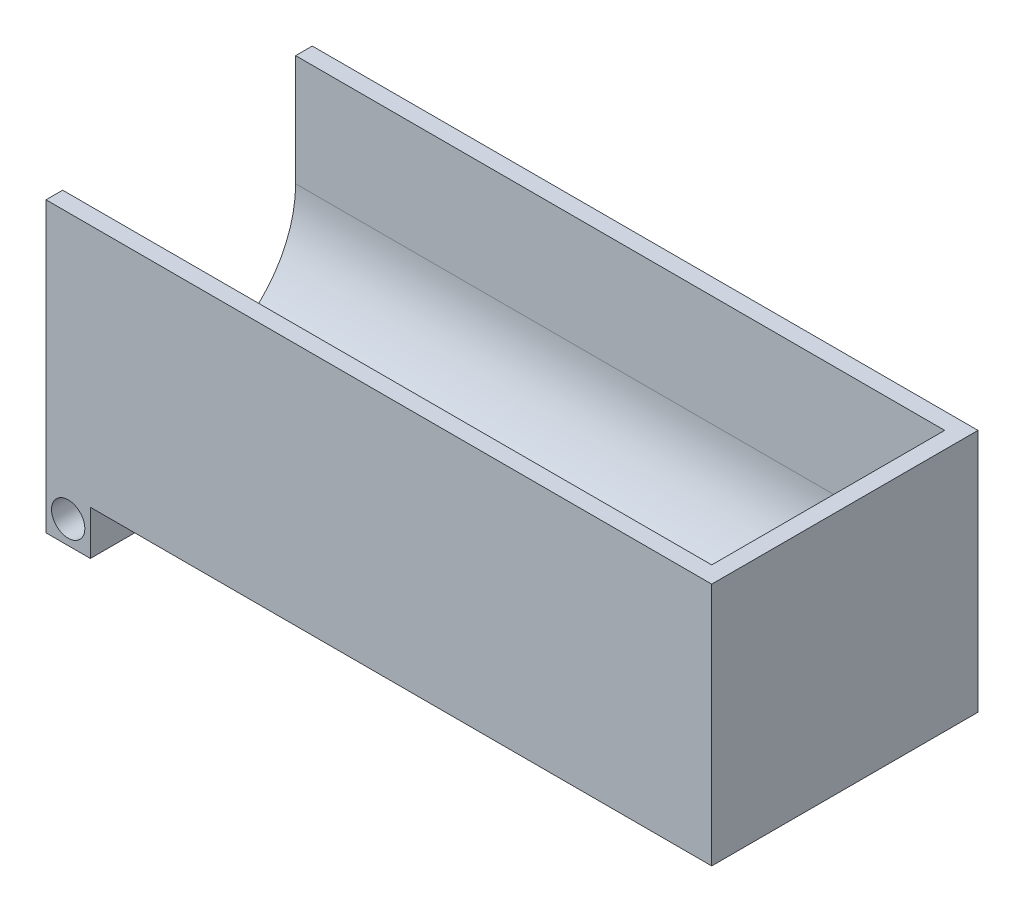
SolidWorks part; units mm, degrees
ref_plane "Front Plane" through (0, 0, 0) normal (0, 0, 1) x (1, 0, 0)
ref_plane "Top Plane" through (0, 0, 0) normal (0, 1, 0) x (1, 0, 0)
ref_plane "Right Plane" through (0, 0, 0) normal (1, 0, 0) x (0, 0, -1)
sketch "Sketch1" plane through (0, 0, 0) normal (1, 0, 0) x (0, 0, -1)
  line L0 (21, 0) -> (24, 0)
  line L1 (24, 0) -> (24, -24)
  line L2 (24, -24) -> (-24, -24)
  line L3 (-24, -24) -> (-24, 0)
  line L4 (-24, 0) -> (-21, 0)
  arc A0 (21, 0) -> (-21, 0) centre (0, 0) cw
  dimension "D3" = 21
  dimension "D1" = 3
  dimension "D2" = 3
  dimension "D4" = 24
extrude "Boss-Extrude1" add sketch "Sketch1" along normal blind 120
sketch "Sketch2" plane through (0, 0, 24) normal (0, 0, 1) x (1, 0, 0)
  line L1 (0, -24) -> (8, -24)
  line L2 (0, -24) -> (0, -32)
  line L3 (0, -32) -> (8, -32)
  line L4 (8, -24) -> (8, -32)
  dimension "D1" = 8
  dimension "D2" = 8
extrude "Boss-Extrude2" add sketch "Sketch2" against normal blind 48
sketch "Sketch3" plane through (0, 0, 24) normal (0, 0, 1) x (1, 0, 0)
  line L0 (0, -32) -> (8, -32) construction
  circle A0 centre (4, -27.8358) radius 3
  point P5 (4, -32)
  dimension "D1" = 6
extrude "Cut-Extrude1" cut sketch "Sketch3" against normal up to next
sketch "Sketch4" plane through (120, 0, 0) normal (1, 0, 0) x (0, 0, -1)
  line L1 (24, 0) -> (-24, 0)
  line L2 (24, 0) -> (24, -24)
  line L3 (24, -24) -> (-24, -24)
  line L4 (-24, 0) -> (-24, -24)
extrude "Boss-Extrude3" add sketch "Sketch4" against normal blind 3
sketch "Sketch5" plane through (0, -24, 0) normal (0, -1, 0) x (1, 0, 0)
  line L0 (120, -24) -> (8, -24) construction
  line L1 (15.3705, -13.3) -> (19.6916, -13.3)
  line L2 (15.3705, -13.3) -> (15.3705, -10.3)
  line L3 (15.3705, -10.3) -> (19.6916, -10.3)
  line L4 (19.6916, -13.3) -> (19.6916, -10.3)
  dimension "D1" = 10.7
  dimension "D2" = 3
extrude "Boss-Extrude4" add sketch "Sketch5" along normal blind 5
sketch "Sketch6" plane through (0, 0, -10.3) normal (0, 0, 1) x (1, 0, 0)
  line L0 (19.6916, -29) -> (15.3705, -29) construction
  circle A0 centre (17.5311, -26.5) radius 0.75
  point P4 (17.5311, -29)
  dimension "D1" = 1.5
  dimension "D2" = 2.5
extrude "Cut-Extrude2" cut sketch "Sketch6" against normal through all
sketch "Sketch7" plane through (0, 0, 0) normal (0, 1, 0) x (1, 0, 0)
  line L8 (120, 24) -> (0, 24)
  line L9 (0, 24) -> (0, 21)
  line L10 (0, 21) -> (117, 21)
  line L11 (117, 21) -> (117, -21)
  line L12 (117, -21) -> (0, -21)
  line L13 (0, -21) -> (0, -24)
  line L14 (0, -24) -> (120, -24)
  line L15 (120, -24) -> (120, 24)
  line L16 (120, 24) -> (0, 24)
  line L17 (0, 24) -> (0, 21)
  line L18 (0, 21) -> (117, 21)
  line L19 (117, 21) -> (117, -21)
  line L20 (117, -21) -> (0, -21)
  line L21 (0, -21) -> (0, -24)
  line L22 (0, -24) -> (120, -24)
  line L23 (120, -24) -> (120, 24)
  dimension "D1" = 0
extrude "Boss-Extrude5" add sketch "Sketch7" along normal blind 20
